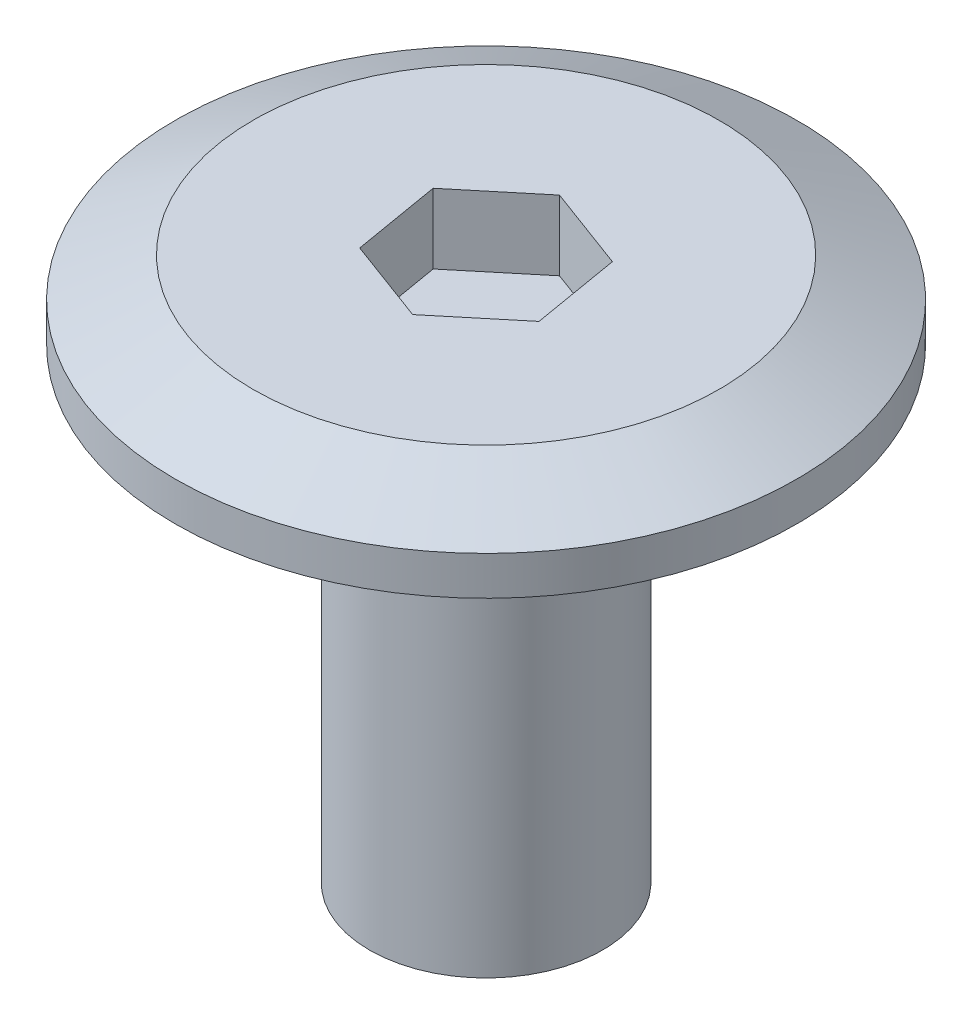
SolidWorks part; units mm, degrees
ref_plane "Front Plane" through (0, 0, 0) normal (0, 0, 1) x (1, 0, 0)
ref_plane "Top Plane" through (0, 0, 0) normal (0, 1, 0) x (1, 0, 0)
ref_plane "Right Plane" through (0, 0, 0) normal (1, 0, 0) x (0, 0, -1)
sketch "Sketch1" plane through (0, 0, 0) normal (0, 1, 0) x (1, 0, 0)
  circle A0 centre (0, 0) radius 4
  dimension "D1" = 8
extrude "Boss-Extrude1" add sketch "Sketch1" along normal blind 1
chamfer "Chamfer1" distance 0.5 distance2 1 1 edges at (0, 1, 4)
sketch "Sketch2" plane through (0, 1, 0) normal (0, 1, 0) x (1, 0, 0)
  line L1 (0.889, 0.7369) -> (-0.1936, 1.1384)
  line L2 (-0.1936, 1.1384) -> (-1.0826, 0.4015)
  line L3 (-1.0826, 0.4015) -> (-0.889, -0.7369)
  line L4 (-0.889, -0.7369) -> (0.1936, -1.1384)
  line L5 (0.1936, -1.1384) -> (1.0826, -0.4015)
  line L6 (1.0826, -0.4015) -> (0.889, 0.7369)
  circle A0 centre (0, 0) radius 1 construction
  dimension "D1" = 2
extrude "Cut-Extrude1" cut sketch "Sketch2" against normal blind 0.9
sketch "Sketch3" plane through (0, 0, 0) normal (0, -1, 0) x (1, 0, 0)
  circle A0 centre (0, 0) radius 1.5
  dimension "D1" = 3
extrude "Boss-Extrude2" add sketch "Sketch3" along normal blind 6
